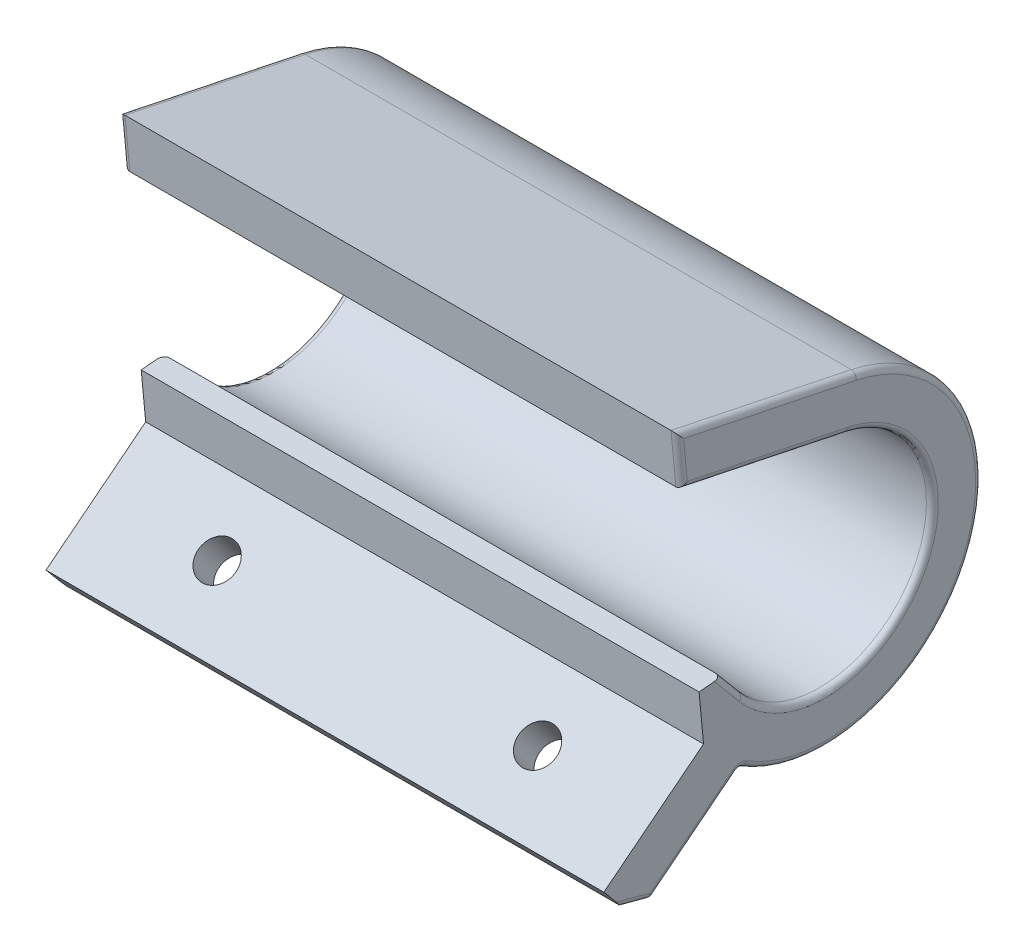
SolidWorks part; units mm, degrees
material "PET"
ref_plane "Plan de face" through (0, 0, 0) normal (0, 0, 1) x (1, 0, 0)
ref_plane "Plan de dessus" through (0, 0, 0) normal (0, 1, 0) x (1, 0, 0)
ref_plane "Plan de droite" through (0, 0, 0) normal (1, 0, 0) x (0, 0, -1)
sketch "Esquisse1" plane through (0, 0, 0) normal (-1, 0, 0) x (0, 0, 1)
  line L0 (-3.0919, -3.2929) -> (4.3772, -9.1761)
  line L1 (4.3772, -9.1761) -> (6.7926, -8.5313)
  line L2 (6.7926, -8.5313) -> (8.3982, -6.6151)
  line L3 (8.3982, -6.6151) -> (0, 0)
  line L4 (-2.0565, 4.1608) -> (2.6974, 4.1608) construction
  line L5 (-12.1055, 16.5299) -> (1.8364, 19.428)
  line L6 (1.8364, 19.428) -> (2.2448, 23.7479)
  line L7 (2.2448, 23.7479) -> (-12.9494, 20.5895)
  line L8 (-3.3754, 1.938) -> (-1.5129, 4.1608)
  line L9 (-1.5129, 4.1608) -> (0.3764, 3.9822)
  line L10 (0.3764, 3.9822) -> (0, 0)
  line L11 (-10.2738, 24.1181) -> (-10.2738, -11.139) construction
  line L12 (0, -1.6985) -> (0, 32.3221) construction
  line L14 (0.3764, 3.9822) -> (62.1013, -1.8523) construction
  line L15 (0, 0) -> (0.3764, 3.9822) construction
  arc A0 (-12.9494, 20.5895) -> (-3.0919, -3.2929) centre (-10.2738, 7.7183) ccw
  arc A1 (-3.3754, 1.938) -> (-12.1055, 16.5299) centre (-10.2738, 7.7183) cw
  dimension "D1" = 9
  dimension "D2" = 4.1463
  dimension "D3" = 4.5
  dimension "D6" = 15.519
  dimension "D7" = 1.8977
  dimension "D8" = 2.9
  dimension "D10" = 2.5
  dimension "D11" = 2.5
extrude "Boss.-Extru.1" add sketch "Esquisse1" along normal up to surface (23.5 mm away) and the other way up to surface (23.5 mm away)
hole_wizard "Fraisage pour vis à tête fraisée M31" positions "Esquisse3" profile "Esquisse2" countersink size "M3" standard "ISO"
sketch "Esquisse3" plane through (0, -3.5351, -2.7845) normal (0, -0.7856, -0.6188) x (-1, 0, 0)
  line L0 (23.5, 0.3913) -> (23.5, -9.1165) construction
  line L1 (-23.5, -10.615) -> (23.5, -10.615) construction
  point P0 (13.5, -5.065)
  dimension "D1" = 10
  dimension "D2" = 5.55
sketch "Esquisse2" plane through (-13.5, -6.6692, 1.1944) normal (1, 0, 0) x (0, 0.6188, -0.7856)
  line L0 (0, 0) -> (0, 10.9614)
  line L1 (0, 10.9614) -> (1.6, 10)
  line L2 (1.6, 10) -> (1.6, 1.7)
  line L3 (1.6, 1.7) -> (2.9, 0.4)
  line L4 (2.9, 0.4) -> (2.9, 0)
  line L6 (2.9, 0) -> (0, 0)
  line L7 (-1.6, 1.7) -> (-2.9, 0.4) construction
  line L10 (0, 10.9614) -> (-1.6, 10) construction
  line L11 (0, -6.35) -> (0, 107.95) construction
  dimension "Diamètre du perçage" = 3.2
  dimension "Profondeur du perçage" = 10
  dimension "Diamètre du fraisage" = 5.8
  dimension "Angle du fraisage" = 90
  dimension "Angle de pointe" = 118
  dimension "Dégagement de la tête" = 0.4
mirror "Symétrie1" about plane through (0, 0, 0) normal (1, 0, 0) of "Fraisage pour vis à tête fraisée M31"
fillet "Congé1" radius 0.5 19 edges at (-23.5, 3.0494, -2.4441) (-23.5, 17.979, -5.1345) (23.5, 3.0494, -2.4441) (23.5, 17.979, -5.1345) (-23.5, 22.1687, -5.3523) (23.5, 22.1687, -5.3523) (-23.5, 3.0975, -17.9971) (23.5, 3.0975, -17.9971) (0, -3.2929, -3.0919) (-23.5, 2.7025, -22.4257) (-23.5, -6.2345, 0.6426) (-23.5, -8.8537, 5.5849) (23.5, -8.8537, 5.5849) (0, -9.1761, 4.3772) (0, -8.5313, 6.7926) (23.5, 2.7025, -22.4257) (23.5, -6.2345, 0.6426) (-23.5, 21.588, 2.0406) (23.5, 21.588, 2.0406)
